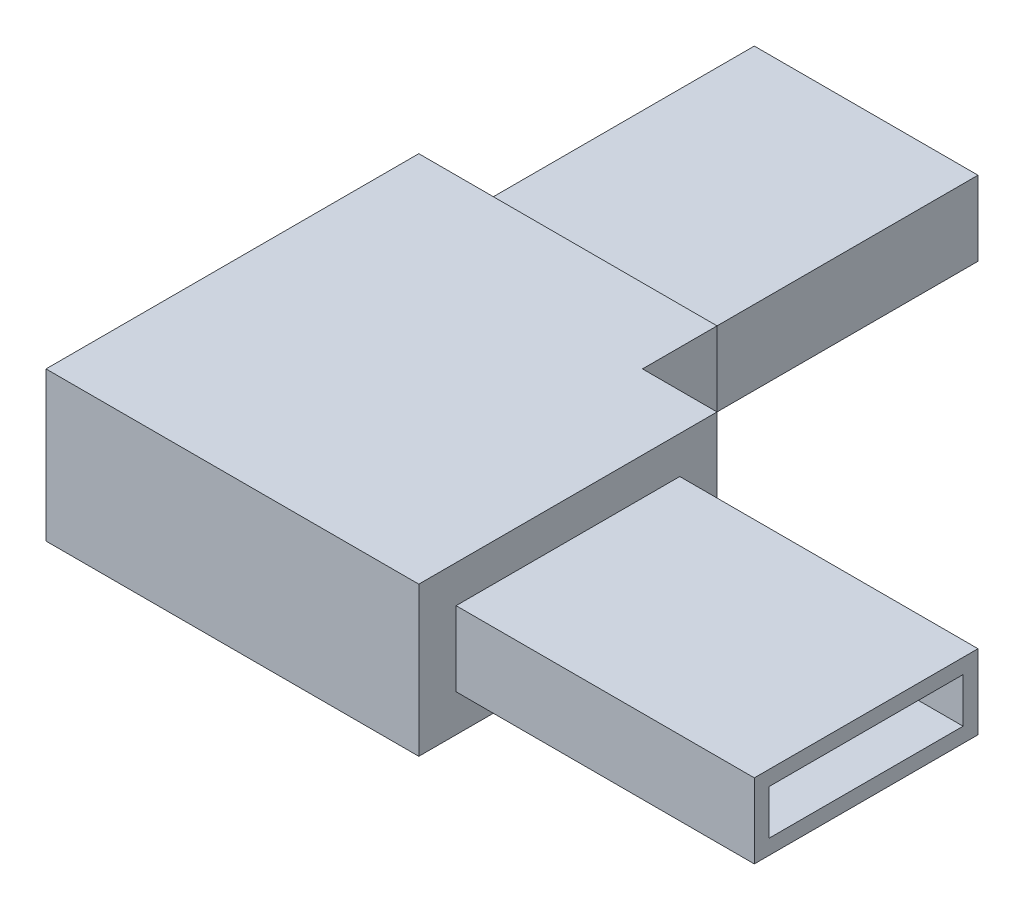
SolidWorks part; units mm, degrees
ref_plane "Alzado" through (0, 0, 0) normal (0, 0, 1) x (1, 0, 0)
ref_plane "Planta" through (0, 0, 0) normal (0, 1, 0) x (1, 0, 0)
ref_plane "Vista lateral" through (0, 0, 0) normal (1, 0, 0) x (0, 0, -1)
sketch "Croquis1" plane through (0, 0, 0) normal (0, 1, 0) x (1, 0, 0)
  line L1 (20, -20) -> (-20, -20)
  line L2 (20, -20) -> (20, 20)
  line L3 (20, 20) -> (-20, 20)
  line L4 (-20, -20) -> (-20, 20)
  line L5 (20, -20) -> (-20, 20) construction
  line L6 (20, 20) -> (-20, -20) construction
  line L7 (20, -20) -> (70, -20)
  line L8 (20, -20) -> (20, 20)
  line L9 (20, 20) -> (70, 20)
  line L10 (70, -20) -> (70, 20)
  line L11 (-20, 20) -> (20, 20)
  line L12 (-20, 20) -> (-20, 70)
  line L13 (-20, 70) -> (20, 70)
  line L14 (20, 20) -> (20, 70)
  point P0 (0, 0)
  dimension "D1" = 40
  dimension "D2" = 40
  dimension "D3" = 50
  dimension "D4" = 50
extrude "Extruir1" add sketch "Croquis1" along normal blind 20 contours L3 L14 L13 L12 | L4 L1 L2 L3 | L7 L10 L9 L2
sketch "Croquis2" plane through (70, 0, 0) normal (1, 0, 0) x (0, 0, -1)
  line L4 (-20, 0) -> (20, 0)
  line L5 (20, 0) -> (20, 20)
  line L6 (20, 20) -> (-20, 20)
  line L7 (-20, 20) -> (-20, 0)
  line L8 (-20, 0) -> (20, 0)
  line L9 (20, 0) -> (20, 20)
  line L10 (20, 20) -> (-20, 20)
  line L11 (-20, 20) -> (-20, 0)
  line L16 (-15, 5) -> (15, 5)
  line L17 (15, 5) -> (15, 15)
  line L18 (15, 15) -> (-15, 15)
  line L19 (-15, 15) -> (-15, 5)
  line L20 (-15, 5) -> (15, 5)
  line L21 (15, 5) -> (15, 15)
  line L22 (15, 15) -> (-15, 15)
  line L23 (-15, 15) -> (-15, 5)
  dimension "D1" = 0
  dimension "D2" = 5
extrude "Extruir2" cut sketch "Croquis2" against normal blind 40
sketch "Croquis3" plane through (0, 0, -70) normal (0, 0, -1) x (-1, 0, 0)
  line L0 (-15, 5) -> (15, 5)
  line L1 (15, 5) -> (15, 15)
  line L2 (15, 15) -> (-15, 15)
  line L3 (-15, 15) -> (-15, 5)
  line L4 (-20, 0) -> (20, 0)
  line L5 (20, 0) -> (20, 20)
  line L6 (20, 20) -> (-20, 20)
  line L7 (-20, 20) -> (-20, 0)
  line L8 (-20, 0) -> (20, 0)
  line L9 (20, 0) -> (20, 20)
  line L10 (20, 20) -> (-20, 20)
  line L11 (-20, 20) -> (-20, 0)
  dimension "D1" = 0
  dimension "D2" = 5
extrude "Extruir3" cut sketch "Croquis3" against normal blind 40
shell "Vaciado1" thickness 2
sketch "Croquis5" plane through (-20, 0, 0) normal (-1, 0, 0) x (0, 0, 1)
  line L0 (-5, 20) -> (-5, 0) construction
  line L2 (20, 20) -> (-30, 20) construction
  line L4 (20, 0) -> (-30, 0) construction
  line L5 (-5, 10) -> (20, 10) construction
  line L6 (20, 20) -> (20, 0) construction
  circle A0 centre (-5, 10) radius 5
  dimension "D1" = 10
extrude "Extruir4" cut sketch "Croquis5" against normal blind 10
